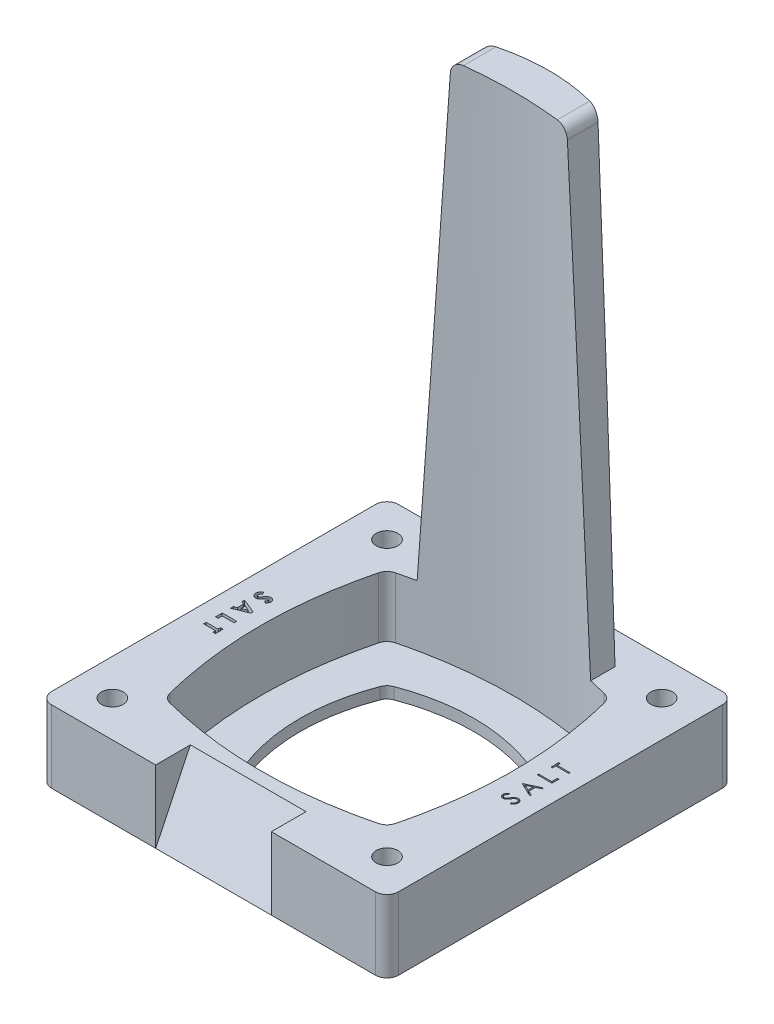
SolidWorks part; units mm, degrees
ref_plane "Front Plane" through (0, 0, 0) normal (0, 0, 1) x (1, 0, 0)
ref_plane "Top Plane" through (0, 0, 0) normal (0, 1, 0) x (1, 0, 0)
ref_plane "Right Plane" through (0, 0, 0) normal (1, 0, 0) x (0, 0, -1)
sketch "Sketch1" plane through (0, 0, 0) normal (0, 1, 0) x (1, 0, 0)
  line L1 (-38.1, -38.1) -> (38.1, -38.1)
  line L2 (-38.1, -38.1) -> (-38.1, 38.1)
  line L3 (-38.1, 38.1) -> (38.1, 38.1)
  line L4 (38.1, -38.1) -> (38.1, 38.1)
  line L5 (-38.1, -38.1) -> (38.1, 38.1) construction
  line L6 (-38.1, 38.1) -> (38.1, -38.1) construction
  point P0 (0, 0)
  dimension "D1" = 76.2
  dimension "D2" = 76.2
extrude "Boss-Extrude1" add sketch "Sketch1" along normal blind 15.875
sketch "Sketch2" plane through (0, 15.875, 0) normal (0, 1, 0) x (1, 0, 0)
  line L0 (-27.686, 0) -> (29.454, 0) construction
  line L1 (-24.384, -24.384) -> (24.384, -24.384) construction
  line L2 (-24.384, -24.384) -> (-24.384, 24.384) construction
  line L3 (-24.384, 24.384) -> (24.384, 24.384) construction
  line L4 (24.384, -24.384) -> (24.384, 24.384) construction
  line L5 (-24.384, -24.384) -> (24.384, 24.384) construction
  line L6 (-24.384, 24.384) -> (24.384, -24.384) construction
  line L7 (-27.686, -27.686) -> (27.686, -27.686) construction
  line L8 (-27.686, -27.686) -> (-27.686, 27.686) construction
  line L9 (-27.686, 27.686) -> (27.686, 27.686) construction
  line L10 (27.686, -27.686) -> (27.686, 27.686) construction
  line L11 (-27.686, -27.686) -> (27.686, 27.686) construction
  line L12 (-27.686, 27.686) -> (27.686, -27.686) construction
  line L13 (0, 27.686) -> (0, -27.686) construction
  spline S0 degree 2 poles (-24.384, 24.384) (-30.988, 0) (-24.384, -24.384) knots 0 0 0 1 1 1
  spline S1 degree 2 poles (-24.384, 24.384) (0, 30.988) (24.384, 24.384) knots 0 0 0 1 1 1
  spline S2 degree 2 poles (24.384, 24.384) (30.988, 0) (24.384, -24.384) knots 0 0 0 1 1 1
  spline S3 degree 2 poles (24.384, -24.384) (0, -30.988) (-24.384, -24.384) knots 0 0 0 1 1 1
  point P0 (0, 0)
  point P6 (0, 0)
  dimension "D1" = 48.768
  dimension "D2" = 48.768
  dimension "D3" = 55.372
  dimension "D4" = 55.372
extrude "Cut-Extrude1" cut sketch "Sketch2" against normal blind 13.335
sketch "Sketch4" plane through (0, 15.875, 0) normal (0, 1, 0) x (1, 0, 0)
  line L1 (-30.1625, -30.1625) -> (30.1625, -30.1625) construction
  line L2 (-30.1625, -30.1625) -> (-30.1625, 30.1625) construction
  line L3 (-30.1625, 30.1625) -> (30.1625, 30.1625) construction
  line L4 (30.1625, -30.1625) -> (30.1625, 30.1625) construction
  line L5 (-30.1625, -30.1625) -> (30.1625, 30.1625) construction
  line L6 (-30.1625, 30.1625) -> (30.1625, -30.1625) construction
  circle A0 centre (-30.1625, 30.1625) radius 2.3813
  circle A1 centre (30.1625, 30.1625) radius 2.3812
  circle A2 centre (30.1625, -30.1625) radius 2.3812
  circle A3 centre (-30.1625, -30.1625) radius 2.3813
  point P0 (0, 0)
  dimension "D3" = 4.7625
  dimension "D4" = 4.7625
  dimension "D5" = 4.7625
  dimension "D6" = 4.7625
  dimension "D1" = 60.325
  dimension "D2" = 60.325
extrude "Cut-Extrude3" cut sketch "Sketch4" against normal through all
fillet "Fillet2" radius 2.54 4 edges at (-38.1, 7.9375, 38.1) (38.1, 7.9375, 38.1) (38.1, 7.9375, -38.1) (-38.1, 7.9375, -38.1)
sketch "Sketch8" plane through (0, 2.54, 0) normal (0, 1, 0) x (1, 0, 0)
  line L0 (-19.05, 0) -> (29.3905, 0) construction
  line L1 (-15.875, -15.875) -> (15.875, -15.875) construction
  line L2 (-15.875, -15.875) -> (-15.875, 15.875) construction
  line L3 (-15.875, 15.875) -> (15.875, 15.875) construction
  line L4 (15.875, -15.875) -> (15.875, 15.875) construction
  line L5 (-15.875, -15.875) -> (15.875, 15.875) construction
  line L6 (-15.875, 15.875) -> (15.875, -15.875) construction
  line L7 (-19.05, -19.05) -> (19.05, -19.05) construction
  line L8 (-19.05, -19.05) -> (-19.05, 19.05) construction
  line L9 (-19.05, 19.05) -> (19.05, 19.05) construction
  line L10 (19.05, -19.05) -> (19.05, 19.05) construction
  line L11 (-19.05, -19.05) -> (19.05, 19.05) construction
  line L12 (-19.05, 19.05) -> (19.05, -19.05) construction
  line L13 (0, 19.05) -> (0, -19.05) construction
  spline S0 degree 2 poles (-15.875, 15.875) (-22.225, 0) (-15.875, -15.875) knots 0 0 0 1 1 1
  spline S1 degree 2 poles (-15.875, 15.875) (0, 22.225) (15.875, 15.875) knots 0 0 0 1 1 1
  spline S2 degree 2 poles (15.875, 15.875) (22.225, 0) (15.875, -15.875) knots 0 0 0 1 1 1
  spline S3 degree 2 poles (15.875, -15.875) (0, -22.225) (-15.875, -15.875) knots 0 0 0 1 1 1
  point P0 (0, 0)
  point P5 (0, 0)
  dimension "D1" = 38.1
  dimension "D2" = 31.75
  dimension "D3" = 31.75
  dimension "D4" = 38.1
  dimension "D5" = 0
  dimension "D6" = 0
extrude "Cut-Extrude4" cut sketch "Sketch8" against normal through all
fillet "Fillet3" radius 2.54 8 edges at (15.875, 1.27, -15.875) (15.875, 1.27, 15.875) (-15.875, 1.27, 15.875) (-15.875, 1.27, -15.875) (-24.384, 9.2075, -24.384) (-24.384, 9.2075, 24.384) (24.384, 9.2075, 24.384) (24.384, 9.2075, -24.384)
sketch "Sketch9" plane through (0, 15.875, 0) normal (0, 1, 0) x (1, 0, 0)
  line L0 (-26.67, 26.67) -> (-24.384, 24.384)
  line L1 (-27.686, -27.686) -> (27.686, -27.686) construction
  line L2 (-27.686, -27.686) -> (-27.686, 27.686) construction
  line L3 (-27.686, 27.686) -> (27.686, 27.686) construction
  line L4 (27.686, -27.686) -> (27.686, 27.686) construction
  line L5 (-27.686, -27.686) -> (27.686, 27.686) construction
  line L6 (-27.686, 27.686) -> (27.686, -27.686) construction
  line L7 (-24.384, -24.384) -> (24.384, -24.384) construction
  line L8 (-24.384, -24.384) -> (-24.384, 24.384) construction
  line L9 (-24.384, 24.384) -> (24.384, 24.384) construction
  line L10 (24.384, -24.384) -> (24.384, 24.384) construction
  line L11 (-24.384, -24.384) -> (24.384, 24.384) construction
  line L12 (-24.384, 24.384) -> (24.384, -24.384) construction
  line L13 (-30.48, -35.56) -> (30.48, -35.56) construction
  line L14 (-30.48, -35.56) -> (-30.48, 35.56) construction
  line L15 (-30.48, 35.56) -> (30.48, 35.56) construction
  line L16 (30.48, -35.56) -> (30.48, 35.56) construction
  line L17 (-30.48, -35.56) -> (30.48, 35.56) construction
  line L18 (-30.48, 35.56) -> (30.48, -35.56) construction
  line L19 (26.67, -26.67) -> (-26.67, -26.67) construction
  line L20 (26.67, -26.67) -> (26.67, 26.67) construction
  line L21 (26.67, 26.67) -> (-26.67, 26.67) construction
  line L22 (-26.67, -26.67) -> (-26.67, 26.67) construction
  line L23 (26.67, -26.67) -> (-26.67, 26.67) construction
  line L24 (26.67, 26.67) -> (-26.67, -26.67) construction
  line L25 (26.67, 26.67) -> (24.384, 24.384)
  spline S0 degree 2 poles (-24.384, 24.384) (0, 30.988) (24.384, 24.384) knots 0 0 0 1 1 1
  spline S1 degree 2 poles (-26.67, 26.67) (0, 44.45) (26.67, 26.67) knots 0 0 0 1 1 1
  point P0 (0, 0)
  point P6 (0, 0)
  point P12 (0, 0)
  point P17 (0, 0)
  dimension "D1" = 55.372
  dimension "D2" = 55.372
  dimension "D3" = 48.768
  dimension "D4" = 48.768
  dimension "D5" = 71.12
  dimension "D6" = 60.96
  dimension "D7" = 53.34
  dimension "D8" = 53.34
extrude "Boss-Extrude2" add sketch "Sketch9" along normal blind 101.6
sketch "Sketch10" plane through (0, 0, 0) normal (0, 0, 1) x (1, 0, 0)
  line L0 (0, 122.457) -> (0, 0) construction
  line L1 (-12.7, 117.475) -> (-19.05, 15.875)
  line L2 (24.384, 117.475) -> (-24.384, 117.475) construction
  line L3 (-35.56, 15.875) -> (35.56, 15.875) construction
  line L4 (12.7, 117.475) -> (19.05, 15.875)
  line L7 (-12.7, 117.475) -> (-26.67, 117.475)
  line L8 (-26.67, 117.475) -> (-26.67, 15.875)
  line L9 (-26.67, 15.875) -> (-19.05, 15.875)
  line L10 (12.7, 117.475) -> (26.67, 117.475)
  line L11 (26.67, 117.475) -> (26.67, 15.875)
  line L12 (26.67, 15.875) -> (19.05, 15.875)
  dimension "D1" = 12.7
  dimension "D2" = 19.05
extrude "Cut-Extrude5" cut sketch "Sketch10" against normal through all
fillet "Fillet4" radius 2.54 2 edges at (12.7, 117.475, -30.1672) (-12.7, 117.475, -30.1672)
sketch "Sketch11" plane through (0, 0, 0) normal (1, 0, 0) x (0, 0, -1)
  line L0 (-30.48, 15.875) -> (-38.1, 0)
  line L1 (35.56, 15.875) -> (-35.56, 15.875) construction
  line L2 (-38.1, 0) -> (-38.1, 15.875)
  line L3 (-38.1, 15.875) -> (-30.48, 15.875)
  dimension "D1" = 7.62
extrude "Cut-Extrude6" cut sketch "Sketch11" against normal mid plane 25.4
sketch "Sketch12" plane through (0, 15.875, 0) normal (0, 1, 0) x (1, 0, 0)
  line L0 (-34.29, 23.8125) -> (-34.29, -23.8125) construction
  line L1 (-38.1, 35.56) -> (-38.1, -35.56) construction
  line L2 (0, 7.4868) -> (0, -6.0106) construction
  line L3 (34.29, 23.8125) -> (34.29, -23.8125) construction
  circle A0 centre (-30.1625, 30.1625) radius 2.3813 construction
  circle A1 centre (-30.1625, -30.1625) radius 2.3813 construction
  text T0 "<b>SALT</b>" font "Century Gothic" height 3.175
  text T1 "SALT" font "Century Gothic" height 3.175
  dimension "D1" = 6.35
  dimension "D2" = 6.35
  dimension "D3" = 3.81
extrude "Cut-Extrude7" cut sketch "Sketch12" against normal blind 1.27
